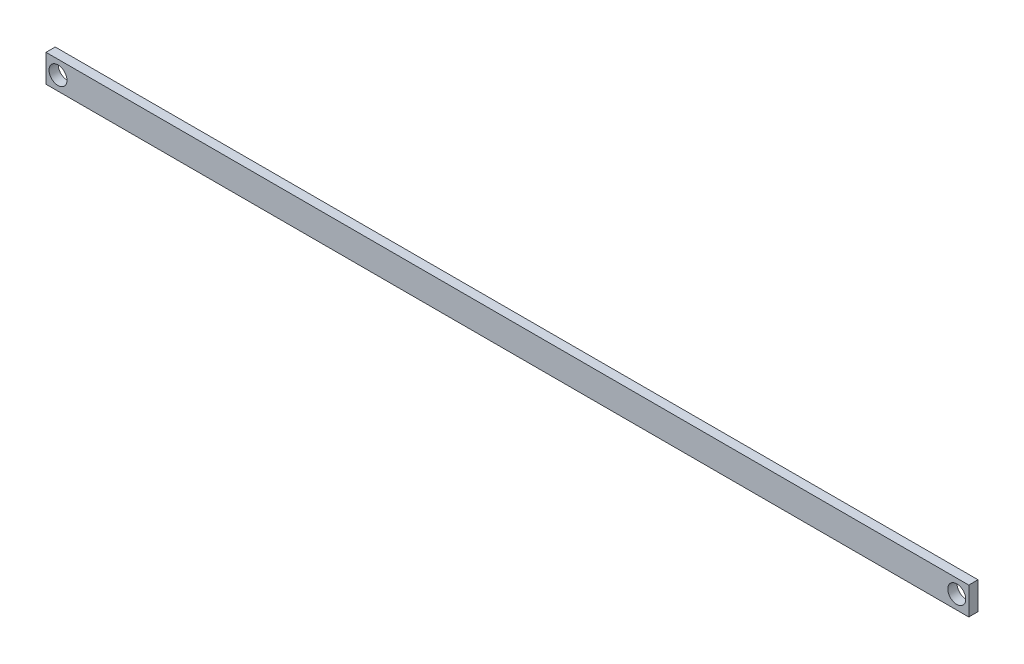
SolidWorks part; units mm, degrees
material "Plain Carbon Steel"
ref_plane "Front Plane" through (0, 0, 0) normal (0, 0, 1) x (1, 0, 0)
ref_plane "Top Plane" through (0, 0, 0) normal (0, 1, 0) x (1, 0, 0)
ref_plane "Right Plane" through (0, 0, 0) normal (1, 0, 0) x (0, 0, -1)
sketch "Sketch2" plane through (0, 0, 0) normal (0, 0, 1) x (1, 0, 0)
  line L0 (0, 0) -> (500, 0)
  line L1 (0, 0) -> (0, -15)
  line L2 (0, -15) -> (500, -15)
  line L3 (500, -15) -> (500, 0)
  dimension "D1" = 500
  dimension "D2" = 15
extrude "Boss-Extrude1" add sketch "Sketch2" against normal blind 5
sketch "Sketch3" plane through (0, 0, 0) normal (0, 0, 1) x (1, 0, 0)
  line L0 (0, 0) -> (0, -15) construction
  line L1 (500, -15) -> (500, 0) construction
  circle A0 centre (6.5, -7.5) radius 4.85
  circle A1 centre (493.5, -7.5) radius 4.85
  dimension "D1" = 9.7
  dimension "D3" = 9.7
  dimension "D2" = 6.5
  dimension "D4" = 6.5
extrude "Cut-Extrude1" cut sketch "Sketch3" against normal blind 5 contours A0 | A1
